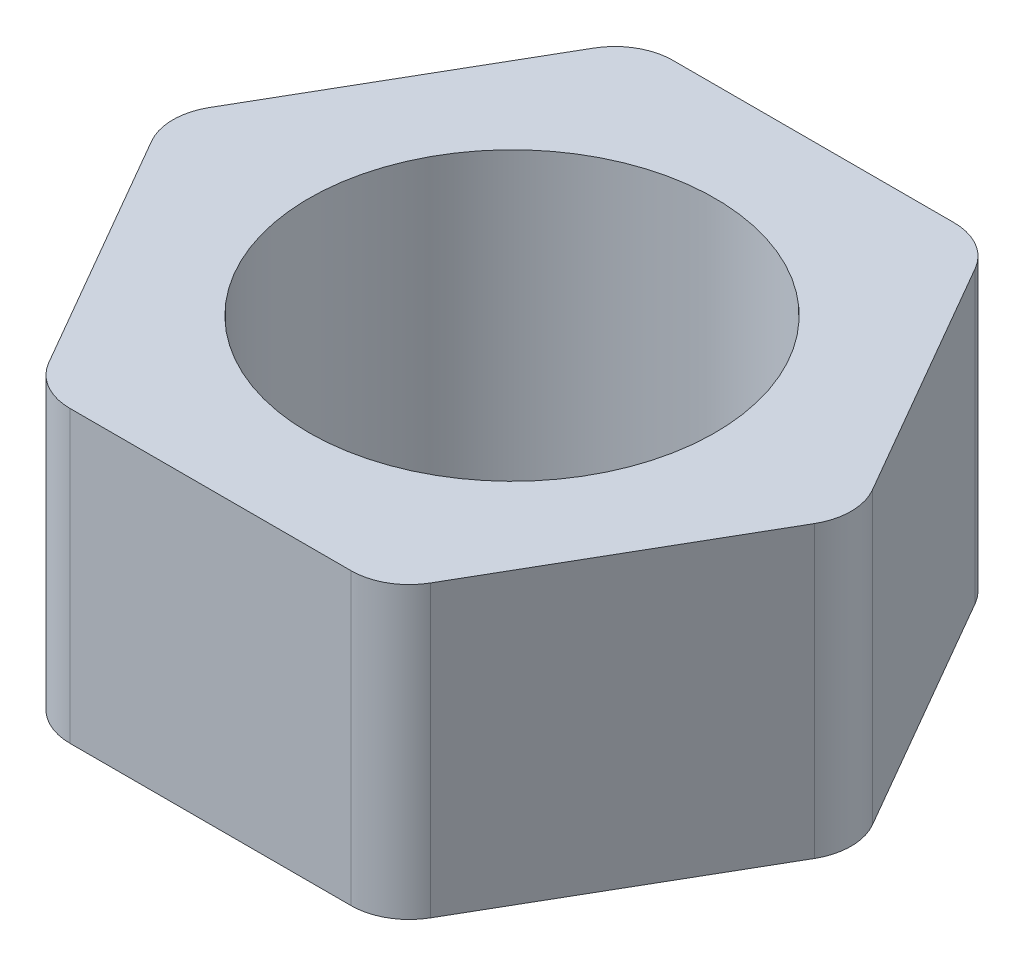
SolidWorks part; units mm, degrees
material "Manual Density from Real Component Viti e dadi"
ref_plane "Piano frontale" through (0, 0, 0) normal (0, 0, 1) x (1, 0, 0)
ref_plane "Piano superiore" through (0, 0, 0) normal (0, 1, 0) x (1, 0, 0)
ref_plane "Piano destro" through (0, 0, 0) normal (1, 0, 0) x (0, 0, -1)
sketch "Schizzo1" plane through (0, 0, 0) normal (0, 1, 0) x (1, 0, 0)
  line L1 (-1.5, 2.5981) -> (-3, 0)
  line L2 (-3, 0) -> (-1.5, -2.5981)
  line L3 (-1.5, -2.5981) -> (1.5, -2.5981)
  line L4 (1.5, -2.5981) -> (3, 0)
  line L5 (3, 0) -> (1.5, 2.5981)
  line L6 (1.5, 2.5981) -> (-1.5, 2.5981)
  circle A0 centre (0, 0) radius 2.5981 construction
  circle A1 centre (0, 0) radius 1.75
  dimension "D2" = 3.5
  dimension "D1" = 3
extrude "Estrusione-Estrusione1" add sketch "Schizzo1" along normal blind 2.5
fillet "Raccordo1" radius 0.5 6 edges at (1.5, 1.25, -2.5981) (-1.5, 1.25, -2.5981) (-3, 1.25, 0) (-1.5, 1.25, 2.5981) (3, 1.25, 0) (1.5, 1.25, 2.5981)
